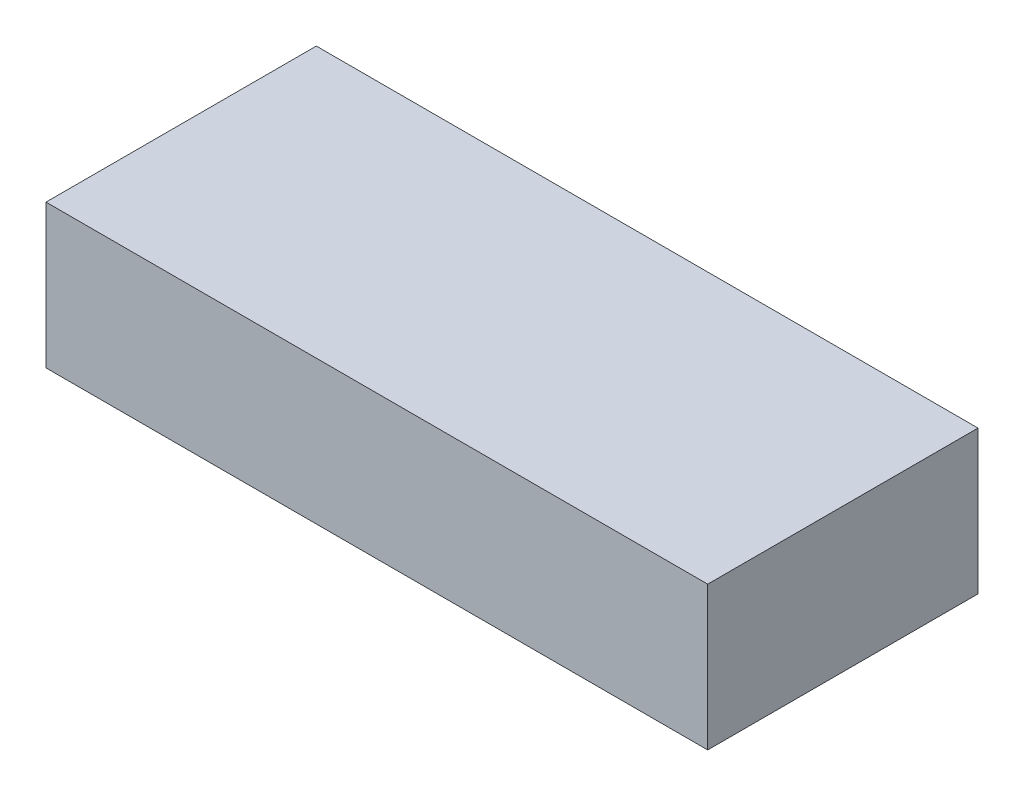
SolidWorks part; units mm, degrees
ref_plane "Front" through (0, 0, 0) normal (0, 0, 1) x (1, 0, 0)
ref_plane "Top" through (0, 0, 0) normal (0, 1, 0) x (1, 0, 0)
ref_plane "Right" through (0, 0, 0) normal (1, 0, 0) x (0, 0, -1)
sketch "ｽｹｯﾁ1" plane through (0, 0, 0) normal (0, 0, 1) x (1, 0, 0)
  line L1 (-117.5, -25.5) -> (117.5, -25.5)
  line L2 (-117.5, -25.5) -> (-117.5, 25.5)
  line L3 (-117.5, 25.5) -> (117.5, 25.5)
  line L4 (117.5, -25.5) -> (117.5, 25.5)
  line L5 (-117.5, -25.5) -> (117.5, 25.5) construction
  line L6 (-117.5, 25.5) -> (117.5, -25.5) construction
  point P0 (0, 0)
  dimension "D1" = 51
  dimension "D2" = 235
extrude "ﾎﾞｽ - 押し出し1" add sketch "ｽｹｯﾁ1" along normal blind 96
